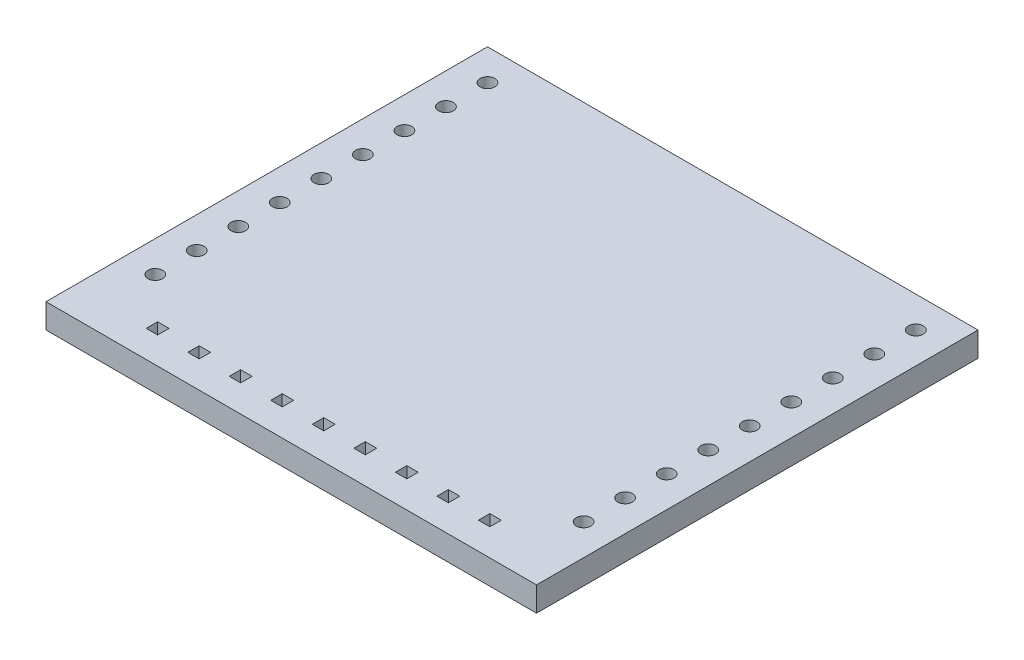
SolidWorks part; units mm, degrees
ref_plane "Спереди" through (0, 0, 0) normal (0, 0, 1) x (1, 0, 0)
ref_plane "Сверху" through (0, 0, 0) normal (0, 1, 0) x (1, 0, 0)
ref_plane "Справа" through (0, 0, 0) normal (1, 0, 0) x (0, 0, -1)
sketch "Эскиз1" plane through (0, 0, 0) normal (0, 1, 0) x (1, 0, 0)
  line L1 (-15, 13.5) -> (15, 13.5)
  line L2 (-15, 13.5) -> (-15, -13.5)
  line L3 (-15, -13.5) -> (15, -13.5)
  line L4 (15, 13.5) -> (15, -13.5)
  line L5 (-15, 13.5) -> (15, -13.5) construction
  line L6 (-15, -13.5) -> (15, 13.5) construction
  point P0 (0, 0)
extrude "Бобышка-Вытянуть1" add sketch "Эскиз1" along normal blind 1.5
sketch "Эскиз2" plane through (0, 1.5, 0) normal (0, 1, 0) x (1, 0, 0)
  line L0 (-15, -13.5) -> (-15, -11.5) construction
  line L1 (-15, 13.5) -> (-15, -13.5) construction
  line L2 (-15, -11.5) -> (-10.174, -11.5) construction
  line L3 (-7.984, -11.15) -> (-7.284, -11.85) construction
  line L4 (-10.524, -11.15) -> (-9.824, -11.15)
  line L5 (-10.524, -11.15) -> (-10.524, -11.85)
  line L6 (-10.524, -11.85) -> (-9.824, -11.85)
  line L7 (-9.824, -11.15) -> (-9.824, -11.85)
  line L8 (-10.524, -11.15) -> (-9.824, -11.85) construction
  line L9 (-10.524, -11.85) -> (-9.824, -11.15) construction
  line L10 (-7.984, -11.85) -> (-7.284, -11.15) construction
  line L11 (-7.984, -11.15) -> (-7.984, -11.85)
  line L12 (-7.984, -11.15) -> (-7.284, -11.15)
  line L13 (-7.284, -11.15) -> (-7.284, -11.85)
  line L14 (-7.984, -11.85) -> (-7.284, -11.85)
  line L15 (-5.444, -11.15) -> (-4.744, -11.85) construction
  line L16 (-5.444, -11.85) -> (-4.744, -11.15) construction
  line L17 (-5.444, -11.15) -> (-5.444, -11.85)
  line L18 (-5.444, -11.15) -> (-4.744, -11.15)
  line L19 (-4.744, -11.15) -> (-4.744, -11.85)
  line L20 (-5.444, -11.85) -> (-4.744, -11.85)
  line L21 (-2.904, -11.15) -> (-2.204, -11.85) construction
  line L22 (-2.904, -11.85) -> (-2.204, -11.15) construction
  line L23 (-2.904, -11.15) -> (-2.904, -11.85)
  line L24 (-2.904, -11.15) -> (-2.204, -11.15)
  line L25 (-2.204, -11.15) -> (-2.204, -11.85)
  line L26 (-2.904, -11.85) -> (-2.204, -11.85)
  line L27 (-0.364, -11.15) -> (0.336, -11.85) construction
  line L28 (-0.364, -11.85) -> (0.336, -11.15) construction
  line L29 (-0.364, -11.15) -> (-0.364, -11.85)
  line L30 (-0.364, -11.15) -> (0.336, -11.15)
  line L31 (0.336, -11.15) -> (0.336, -11.85)
  line L32 (-0.364, -11.85) -> (0.336, -11.85)
  line L33 (2.176, -11.15) -> (2.876, -11.85) construction
  line L34 (2.176, -11.85) -> (2.876, -11.15) construction
  line L35 (2.176, -11.15) -> (2.176, -11.85)
  line L36 (2.176, -11.15) -> (2.876, -11.15)
  line L37 (2.876, -11.15) -> (2.876, -11.85)
  line L38 (2.176, -11.85) -> (2.876, -11.85)
  line L39 (4.716, -11.15) -> (5.416, -11.85) construction
  line L40 (4.716, -11.85) -> (5.416, -11.15) construction
  line L41 (4.716, -11.15) -> (4.716, -11.85)
  line L42 (4.716, -11.15) -> (5.416, -11.15)
  line L43 (5.416, -11.15) -> (5.416, -11.85)
  line L44 (4.716, -11.85) -> (5.416, -11.85)
  line L45 (7.256, -11.15) -> (7.956, -11.85) construction
  line L46 (7.256, -11.85) -> (7.956, -11.15) construction
  line L47 (7.256, -11.15) -> (7.256, -11.85)
  line L48 (7.256, -11.15) -> (7.956, -11.15)
  line L49 (7.956, -11.15) -> (7.956, -11.85)
  line L50 (7.256, -11.85) -> (7.956, -11.85)
  line L51 (9.796, -11.15) -> (10.496, -11.85) construction
  line L52 (9.796, -11.85) -> (10.496, -11.15) construction
  line L53 (9.796, -11.15) -> (9.796, -11.85)
  line L54 (9.796, -11.15) -> (10.496, -11.15)
  line L55 (10.496, -11.15) -> (10.496, -11.85)
  line L56 (9.796, -11.85) -> (10.496, -11.85)
  line L57 (-15, -13.5) -> (-15, -8.72) construction
  line L58 (-15, -8.72) -> (-13.1, -8.72) construction
  line L59 (0, 13.5) -> (0, -13.5) construction
  line L60 (15, 13.5) -> (-15, 13.5) construction
  line L61 (-15, -13.5) -> (15, -13.5) construction
  circle A0 centre (-13.1, -8.72) radius 0.45
  circle A1 centre (-13.1, -6.18) radius 0.45
  circle A2 centre (-13.1, -3.64) radius 0.45
  circle A3 centre (-13.1, -1.1) radius 0.45
  circle A4 centre (-13.1, 1.44) radius 0.45
  circle A5 centre (-13.1, 3.98) radius 0.45
  circle A6 centre (-13.1, 6.52) radius 0.45
  circle A7 centre (-13.1, 9.06) radius 0.45
  circle A8 centre (-13.1, 11.6) radius 0.45
  circle A9 centre (13.1, 11.6) radius 0.45
  circle A10 centre (13.1, 9.06) radius 0.45
  circle A11 centre (13.1, 6.52) radius 0.45
  circle A12 centre (13.1, 3.98) radius 0.45
  circle A13 centre (13.1, 1.44) radius 0.45
  circle A14 centre (13.1, -1.1) radius 0.45
  circle A15 centre (13.1, -3.64) radius 0.45
  circle A16 centre (13.1, -6.18) radius 0.45
  circle A17 centre (13.1, -8.72) radius 0.45
  dimension "D2" = 9
  dimension "D1" = 9
extrude "Вырез-Вытянуть1" cut sketch "Эскиз2" against normal through all
